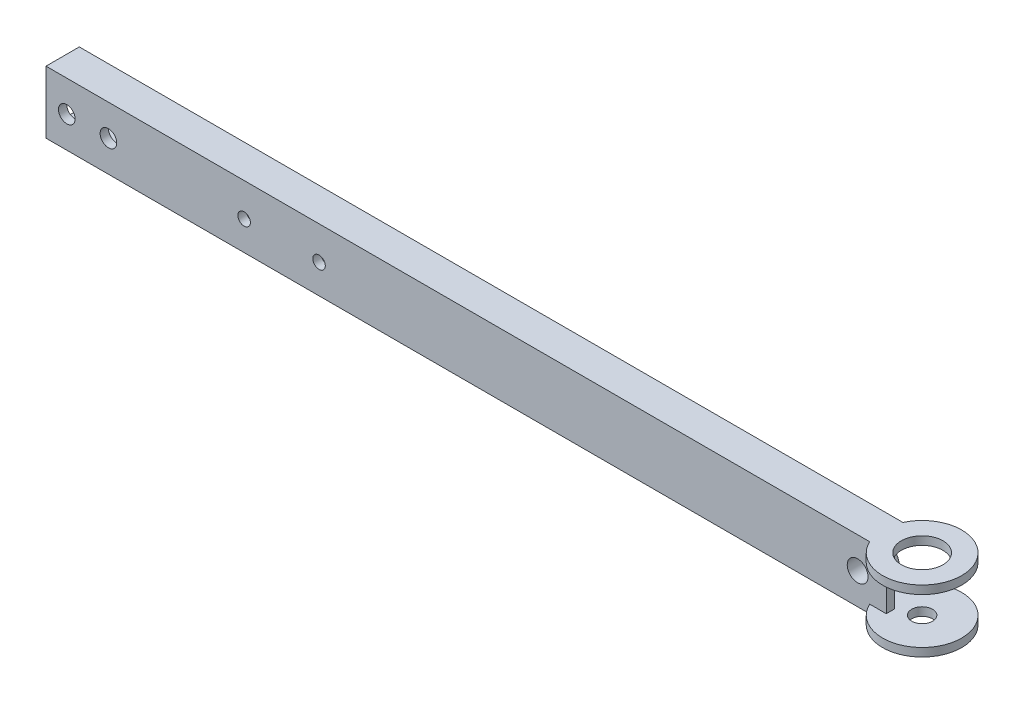
SolidWorks part; units mm, degrees
ref_plane "Front Plane" through (0, 0, 0) normal (0, 0, 1) x (1, 0, 0)
ref_plane "Top Plane" through (0, 0, 0) normal (0, 1, 0) x (1, 0, 0)
ref_plane "Right Plane" through (0, 0, 0) normal (1, 0, 0) x (0, 0, -1)
sketch "Sketch1" plane through (0, 0, 0) normal (0, 1, 0) x (1, 0, 0)
  line L0 (-206.5, 4) -> (-8.6168, 4)
  line L1 (-206.5, 4) -> (-206.5, -4)
  line L2 (-8.6168, -4) -> (-206.5, -4)
  arc A0 (-8.6168, -4) -> (-8.6168, 4) centre (0, 0) ccw
  circle A1 centre (0, 0) radius 2.5
  point P7 (-9.5, 0)
  point P8 (-206.5, 0)
  point P9 (-192, 0)
  point P10 (-176, 0)
  dimension "D2" = 19
  dimension "D3" = 5
  dimension "D1" = 8
  dimension "D4" = 14.5
  dimension "D5" = 16
  dimension "D6" = 176
extrude "Boss-Extrude3" add sketch "Sketch1" along normal blind 2
sketch "Sketch5" plane through (-206.5, 0, 0) normal (-1, 0, 0) x (0, 0, 1)
  line L1 (4, 2) -> (2, 2)
  line L2 (4, 2) -> (4, 13)
  line L3 (4, 13) -> (2, 13)
  line L4 (2, 2) -> (2, 13)
  dimension "D1" = 2
  dimension "D2" = 11
extrude "Boss-Extrude4" add sketch "Sketch5" against normal up to vertex (197.8832 mm away) up to point (-8.6168, 2, 4)
sketch "Sketch6" plane through (0, 13, 0) normal (0, 1, 0) x (1, 0, 0)
  line L1 (-206.5, 4) -> (-8.6168, 4)
  line L2 (-206.5, 4) -> (-206.5, -4)
  line L3 (-206.5, -4) -> (-8.6168, -4)
  arc A0 (-8.6168, 4) -> (-8.6168, -4) centre (0, 0) cw
  circle A1 centre (0, 0) radius 5
  dimension "D1" = 10
extrude "Boss-Extrude5" add sketch "Sketch6" along normal blind 2
sketch "Sketch8" plane through (-8.6168, 0, 0) normal (1, 0, 0) x (0, 0, -1)
  line L4 (-4, 13) -> (-4, 2)
  line L5 (-4, 2) -> (-2, 2)
  line L6 (-2, 2) -> (-2, 13)
  line L7 (-2, 13) -> (-4, 13)
  line L8 (-4, 13) -> (-4, 2)
  line L9 (-4, 2) -> (-2, 2)
  line L10 (-2, 2) -> (-2, 13)
  line L11 (-2, 13) -> (-4, 13)
  dimension "D1" = 0
extrude "Boss-Extrude6" add sketch "Sketch8" along normal blind 4
sketch "Sketch10" plane through (0, 0, 2) normal (0, 0, -1) x (-1, 0, 0)
  line L0 (206.5, 15) -> (206.5, 0) construction
  line L1 (206.5, 0) -> (8.6168, 0) construction
  circle A0 centre (201.5, 7.5) radius 2
  circle A1 centre (191.5, 7.5) radius 2
  circle A2 centre (158.9, 7) radius 1.5
  circle A3 centre (140.9, 7) radius 1.5
  dimension "D3" = 4
  dimension "D4" = 4
  dimension "D5" = 3
  dimension "D6" = 3
  dimension "D1" = 5
  dimension "D2" = 10
  dimension "D7" = 18
  dimension "D8" = 32.6
  dimension "D9" = 7.5
  dimension "D10" = 7
extrude "Cut-Extrude8" cut sketch "Sketch10" against normal up to next
sketch "Sketch11" plane through (0, 0, 2) normal (0, 0, -1) x (-1, 0, 0)
  line L0 (206.5, 13) -> (206.5, 2) construction
  line L3 (8.6168, 0) -> (206.5, 0) construction
  circle A0 centre (11.5, 7.5) radius 4
  circle A1 centre (11.5, 7.5) radius 2.5
  dimension "D1" = 8
  dimension "D2" = 5
  dimension "D3" = 195
  dimension "D4" = 7.5
extrude "Boss-Extrude7" add sketch "Sketch11" along normal blind 4
sketch "Sketch12" plane through (0, 0, 2) normal (0, 0, -1) x (-1, 0, 0)
  circle A2 centre (11.5, 7.5) radius 2.5
  circle A3 centre (11.5, 7.5) radius 2.5
  dimension "D1" = 0
extrude "Cut-Extrude9" cut sketch "Sketch12" against normal up to next
hole_wizard "M3.5x0.6 Tapped Hole2" positions "Sketch15" profile "Sketch16" tap size "M3.5x0.6" standard "ANSI Metric"
sketch "Sketch15" plane through (0, 0, 0) normal (0, -1, 0) x (-1, 0, 0)
  point P0 (192, 0)
  point P3 (176, 0)
sketch "Sketch16" plane through (-192, 0, 0) normal (1, 0, 0) x (0, 0, -1)
  line L0 (0, 0) -> (0, 2.8712)
  line L1 (0, 2.8712) -> (1.45, 2)
  line L2 (1.45, 2) -> (1.45, 0.325)
  line L3 (1.45, 0.325) -> (1.775, 0)
  line L5 (1.775, 0) -> (0, 0)
  line L6 (-1.45, 0.325) -> (-1.775, 0) construction
  line L10 (0, 2.8712) -> (-1.45, 2) construction
  line L11 (0, -6.35) -> (0, 107.95) construction
  dimension "Tap Drill Dia." = 2.9
  dimension "Tap Drill Depth" = 2
  dimension "Near C'Sink Dia." = 3.55
  dimension "Near C'Sink Angle" = 90
  dimension "Drill Angle" = 118
cosmetic thread "Hole Thread1" parameters "D1"=2, "D2"=3.5
cosmetic thread "Hole Thread2" parameters "D1"=2, "D2"=3.5
fillet "Fillet1" radius 1 1 edges at (-15.5, 7.5, 2)
